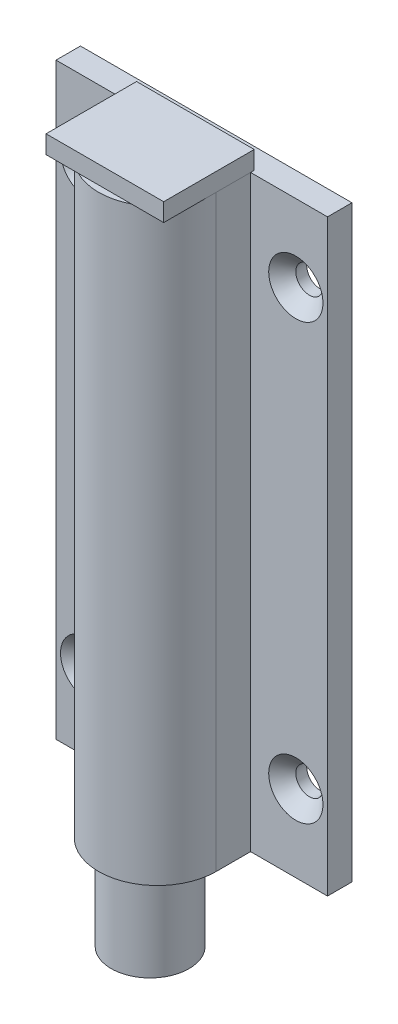
SolidWorks part; units mm, degrees
ref_plane "前视基准面" through (0, 0, 0) normal (0, 0, 1) x (1, 0, 0)
ref_plane "上视基准面" through (0, 0, 0) normal (0, 1, 0) x (1, 0, 0)
ref_plane "右视基准面" through (0, 0, 0) normal (1, 0, 0) x (0, 0, -1)
sketch "草图1" plane through (0, 0, 0) normal (0, 0, 1) x (1, 0, 0)
  line L1 (-15, -32.5) -> (15, -32.5)
  line L2 (-15, -32.5) -> (-15, 32.5)
  line L3 (-15, 32.5) -> (15, 32.5)
  line L4 (15, -32.5) -> (15, 32.5)
  line L5 (-15, -32.5) -> (15, 32.5) construction
  line L6 (-15, 32.5) -> (15, -32.5) construction
  line L7 (-11.5, -24) -> (11.5, -24) construction
  line L8 (-11.5, -24) -> (-11.5, 24) construction
  line L9 (-11.5, 24) -> (11.5, 24) construction
  line L10 (11.5, -24) -> (11.5, 24) construction
  line L11 (-11.5, -24) -> (11.5, 24) construction
  line L12 (-11.5, 24) -> (11.5, -24) construction
  circle A0 centre (-11.5, 24) radius 1.5
  circle A1 centre (11.5, 24) radius 1.5
  circle A2 centre (11.5, -24) radius 1.5
  circle A3 centre (-11.5, -24) radius 1.5
  point P0 (0, 0)
  point P6 (0, 0)
  dimension "D5" = 3
  dimension "D1" = 65
  dimension "D2" = 30
  dimension "D3" = 48
  dimension "D4" = 23
extrude "凸台-拉伸1" add sketch "草图1" along normal blind 2.7
sketch "草图2" plane through (0, -32.5, 0) normal (0, -1, 0) x (1, 0, 0)
  line L0 (0, 2.7) -> (0, 16.7191) construction
  line L1 (-15, 2.7) -> (15, 2.7) construction
  line L2 (-6.5, 2.7) -> (-6.5, 6.5)
  line L3 (6.5, 6.5) -> (6.5, 2.7)
  line L4 (-6.5, 2.7) -> (6.5, 2.7)
  line L5 (-15, 0) -> (15, 0) construction
  arc A0 (-6.5, 6.5) -> (6.5, 6.5) centre (0, 6.5) cw
  circle A1 centre (0, 7.3) radius 4.3
  point P9 (0, 13)
  point P15 (0, 3)
  dimension "D3" = 8.6
  dimension "D1" = 13
  dimension "D2" = 13
  dimension "D4" = 3
extrude "凸台-拉伸2" add sketch "草图2" against normal up to surface (65 mm away) up to face at (0, 32.5, 1.35)
sketch "草图3" plane through (0, -32.5, 0) normal (0, -1, 0) x (1, 0, 0)
  circle A0 centre (0, 7.3) radius 4.3
extrude "凸台-拉伸3" add sketch "草图3" along normal blind 10 separate body
sketch "草图4" plane through (0, 32.5, 0) normal (0, 1, 0) x (1, 0, 0)
  line L0 (6.5, -6.5) -> (6.5, -2.7) construction
  line L1 (-6.5, -12.3) -> (6.5, -12.3)
  line L2 (-6.5, -12.3) -> (-6.5, -2.3)
  line L3 (-6.5, -2.3) -> (6.5, -2.3)
  line L4 (6.5, -12.3) -> (6.5, -2.3)
  line L5 (-6.5, -12.3) -> (6.5, -2.3) construction
  line L6 (-6.5, -2.3) -> (6.5, -12.3) construction
  point P0 (0, -7.3)
  dimension "D1" = 10
extrude "凸台-拉伸4" add sketch "草图4" along normal blind 2 separate body
chamfer "倒角1" distance 1.5 angle 45 4 edges at (13, 24, 2.7) (-10, 24, 2.7) (-10, -24, 2.7) (13, -24, 2.7)
